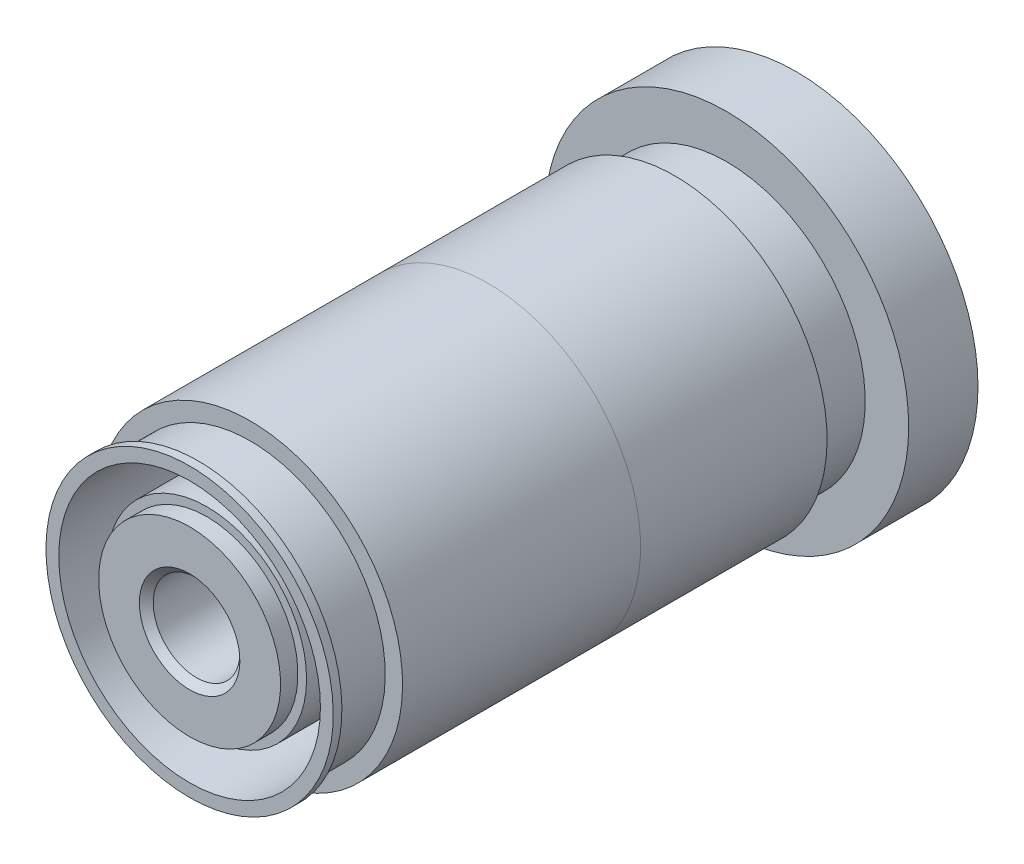
SolidWorks part; units mm, degrees
ref_plane "Front Plane" through (0, 0, 0) normal (0, 0, 1) x (1, 0, 0)
ref_plane "Top Plane" through (0, 0, 0) normal (0, 1, 0) x (1, 0, 0)
ref_plane "Right Plane" through (0, 0, 0) normal (1, 0, 0) x (0, 0, -1)
sketch "Sketch2" plane through (0, 0, 0) normal (1, 0, 0) x (0, 0, -1)
  line L0 (0, 0) -> (426251.7826, 0) construction
  line L1 (0, 0) -> (0, -426251.7826) construction
  line L2 (190, 0) -> (190, 105)
  line L3 (190, 105) -> (150, 105)
  line L7 (150, 79.9) -> (120, 79.9)
  line L8 (120, 79.9) -> (120, 87.9)
  line L9 (120, 87.9) -> (-125, 87.9)
  line L10 (-125, 87.9) -> (-125, 77.9)
  line L11 (-125, 77.9) -> (-155, 77.9)
  line L12 (-155, 77.9) -> (-155, 82.9)
  line L13 (-155, 82.9) -> (-160, 82.9)
  line L14 (-160, 82.9) -> (-160, 75.5)
  line L15 (-160, 75.5) -> (150, 75.5)
  line L16 (150, 75.5) -> (150, 57.5)
  line L17 (150, 57.5) -> (-150, 57.5)
  line L18 (-150, 57.5) -> (-150, 52.5)
  line L19 (-150, 52.5) -> (-160, 52.5)
  line L20 (-160, 52.5) -> (-160, 0)
  line L21 (-160, 0) -> (190, 0)
  line L22 (150, 79.9) -> (150, 105)
  point P7 (210.0105, 79.9)
  dimension "D1" = 57.5
  dimension "D2" = 87.9
  dimension "D3" = 8
  dimension "D4" = 350
  dimension "D5" = 10
  dimension "D6" = 5
  dimension "D7" = 10
  dimension "D8" = 5
  dimension "D9" = 18
  dimension "D10" = 40
  dimension "D11" = 105
  dimension "D12" = 310
  dimension "D13" = 40
  dimension "D14" = 5
  dimension "D15" = 30
  dimension "D16" = 30
  dimension "D17" = 160
revolve "Revolve1" add sketch "Sketch2" angle 360 about L21
ref_plane "Plane1" through (0, 120, 0) normal (0, 1, 0) x (1, 0, 0)
sketch "Sketch3" plane through (0, 120, 0) normal (0, 1, 0) x (1, 0, 0)
  line L0 (-160.0514, 12.389) -> (129.7644, 12.389)
split line "Split Line1"
sketch "Sketch4" plane through (0, 0, -190) normal (0, 0, -1) x (-1, 0, 0)
  circle A0 centre (0, 0) radius 25
  dimension "D1" = 50
extrude "Cut-Extrude1" cut sketch "Sketch4" against normal up to surface (350 mm away) up to face at (0, -52.5, 160)
chamfer "Chamfer1" distance 4 angle 45 1 edges at (0, 25, 160)
